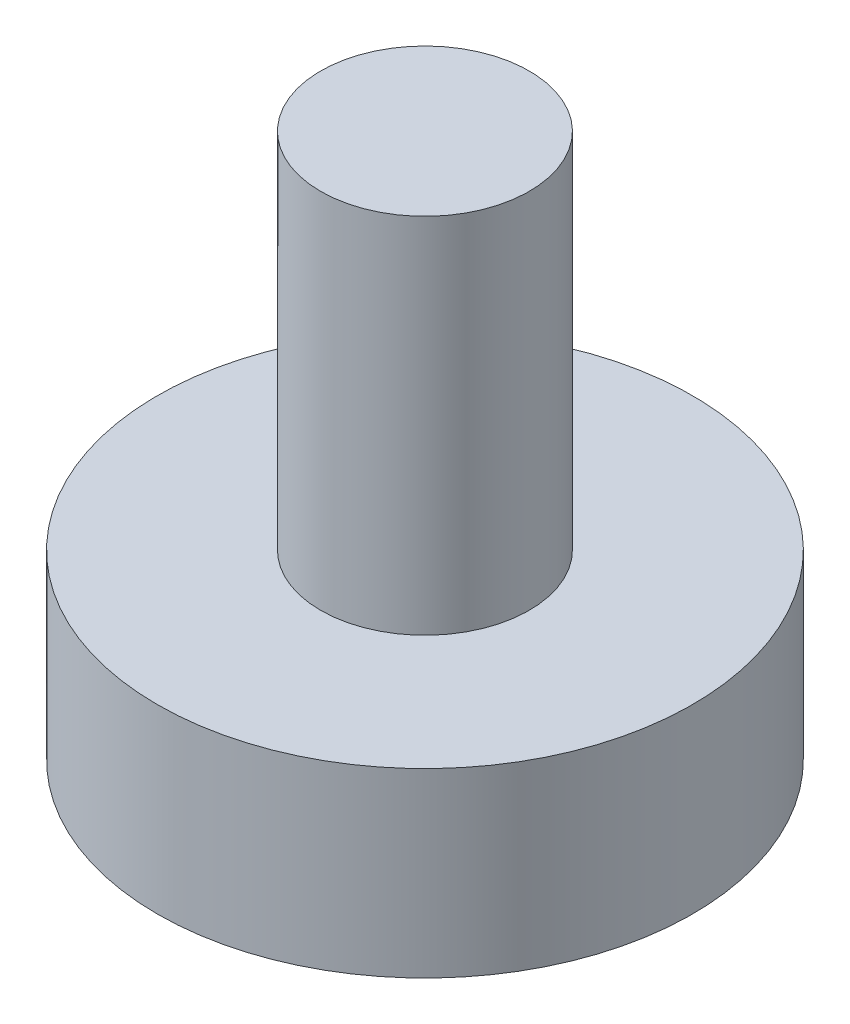
SolidWorks part; units mm, degrees
ref_plane "Front Plane" through (0, 0, 0) normal (0, 0, 1) x (1, 0, 0)
ref_plane "Top Plane" through (0, 0, 0) normal (0, 1, 0) x (1, 0, 0)
ref_plane "Right Plane" through (0, 0, 0) normal (1, 0, 0) x (0, 0, -1)
sketch "Sketch1" plane through (0, 0, 0) normal (0, 1, 0) x (1, 0, 0)
  circle A1 centre (0, 0) radius 2.95
  dimension "D1" = 5.9
extrude "Boss-Extrude1" add sketch "Sketch1" along normal blind 2
sketch "Sketch2" plane through (0, 2, 0) normal (0, 1, 0) x (1, 0, 0)
  circle A0 centre (0, 0) radius 1.15
  dimension "D1" = 2.3
extrude "Boss-Extrude2" add sketch "Sketch2" along normal blind 4
